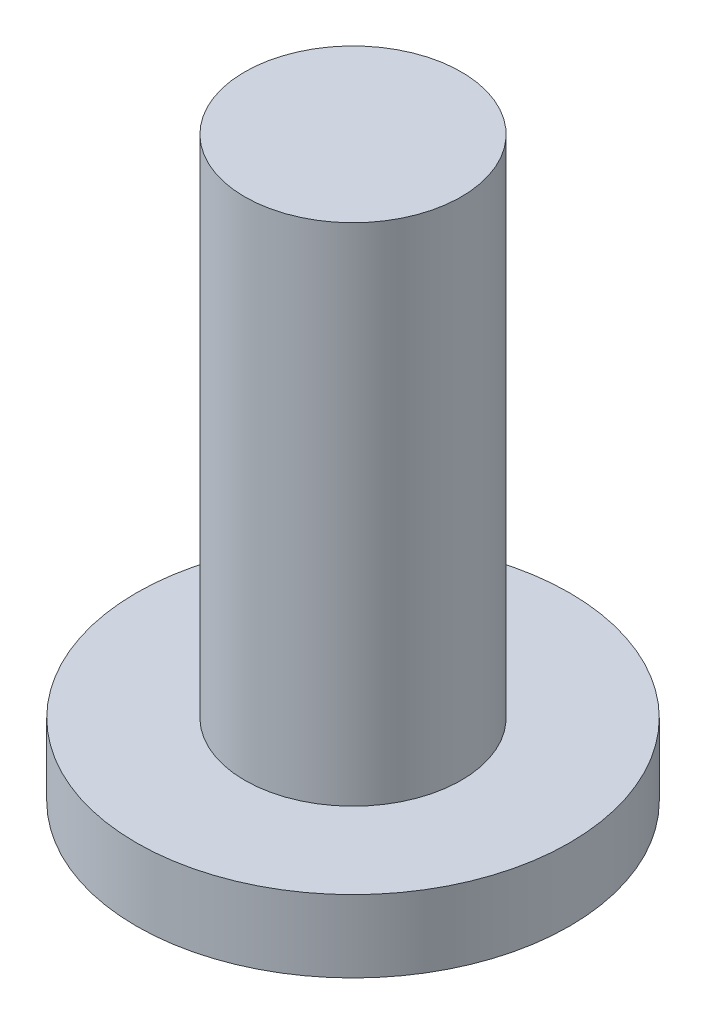
SolidWorks part; units mm, degrees
ref_plane "前视基准面" through (0, 0, 0) normal (0, 0, 1) x (1, 0, 0)
ref_plane "上视基准面" through (0, 0, 0) normal (0, 1, 0) x (1, 0, 0)
ref_plane "右视基准面" through (0, 0, 0) normal (1, 0, 0) x (0, 0, -1)
other "Configuration Table"
sketch "草图1" plane through (0, 0, 0) normal (0, 1, 0) x (1, 0, 0)
  circle A0 centre (0, 0) radius 150
  dimension "D1" = 300
extrude "凸台-拉伸1" add sketch "草图1" along normal blind 50
sketch "草图2" plane through (0, 50, 0) normal (0, 1, 0) x (1, 0, 0)
  circle A0 centre (0, 0) radius 75
  dimension "D1" = 150
extrude "凸台-拉伸2" add sketch "草图2" along normal blind 350
